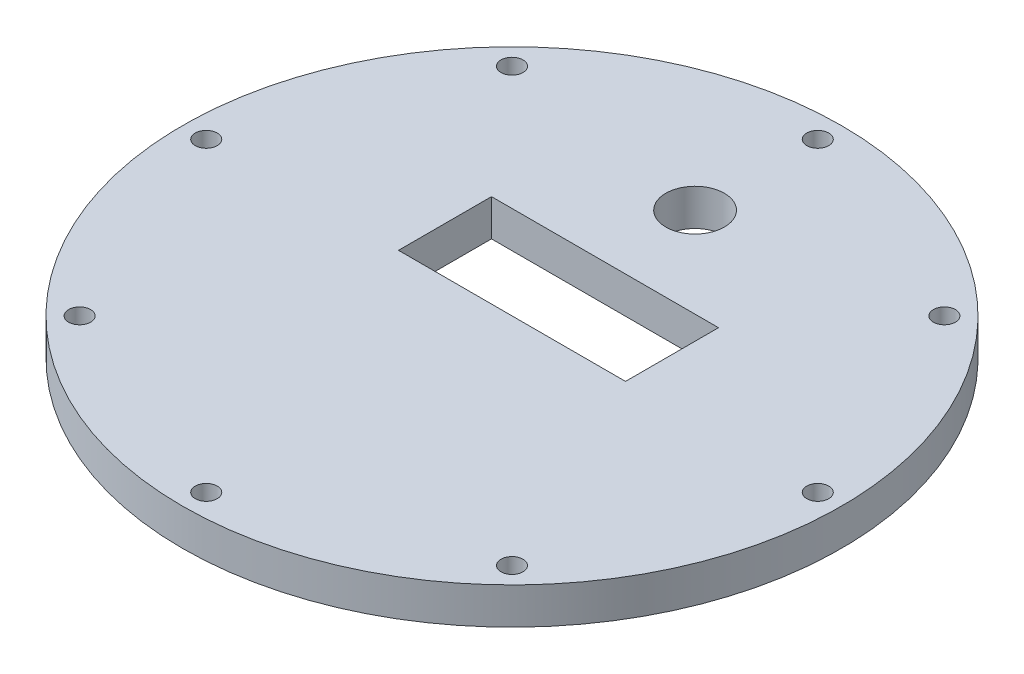
SolidWorks part; units mm, degrees
material "6061-T6 (SS)"
ref_plane "Front Plane" through (0, 0, 0) normal (0, 0, 1) x (1, 0, 0)
ref_plane "Top Plane" through (0, 0, 0) normal (0, 1, 0) x (1, 0, 0)
ref_plane "Right Plane" through (0, 0, 0) normal (1, 0, 0) x (0, 0, -1)
sketch "Sketch1" plane through (0, 0, 0) normal (0, 1, 0) x (1, 0, 0)
  circle A0 centre (0, 0) radius 45
  circle A1 centre (0, 41.75) radius 1.5
  circle A2 centre (29.5217, 29.5217) radius 1.5
  circle A3 centre (41.75, 0) radius 1.5
  circle A4 centre (29.5217, -29.5217) radius 1.5
  circle A5 centre (0, -41.75) radius 1.5
  circle A6 centre (-29.5217, -29.5217) radius 1.5
  circle A7 centre (-41.75, 0) radius 1.5
  circle A8 centre (-29.5217, 29.5217) radius 1.5
  point P22 (0, 0)
  dimension "D1" = 8
extrude "Boss-Extrude2" add sketch "Sketch1" along normal blind 5
sketch "Sketch2" plane through (0, 5, 0) normal (0, 1, 0) x (1, 0, 0)
  line L5 (-15.5, -12.7) -> (15.5, 12.7) construction
  line L6 (-15.5, 12.7) -> (15.5, -12.7) construction
  line L7 (-15.5, 12.7) -> (15.5, 12.7)
  line L8 (-15.5, 12.7) -> (-15.5, 0)
  line L9 (-15.5, 0) -> (15.5, 0)
  line L10 (15.5, 12.7) -> (15.5, 0)
  point P0 (0, 0)
  dimension "D1" = 31
  dimension "D2" = 25.4
extrude "Cut-Extrude2" cut sketch "Sketch2" against normal blind 10
sketch "Sketch4" plane through (0, 5, 0) normal (0, 1, 0) x (1, 0, 0)
  circle A0 centre (0, 25) radius 4
extrude "Cut-Extrude6" cut sketch "Sketch4" against normal blind 10
